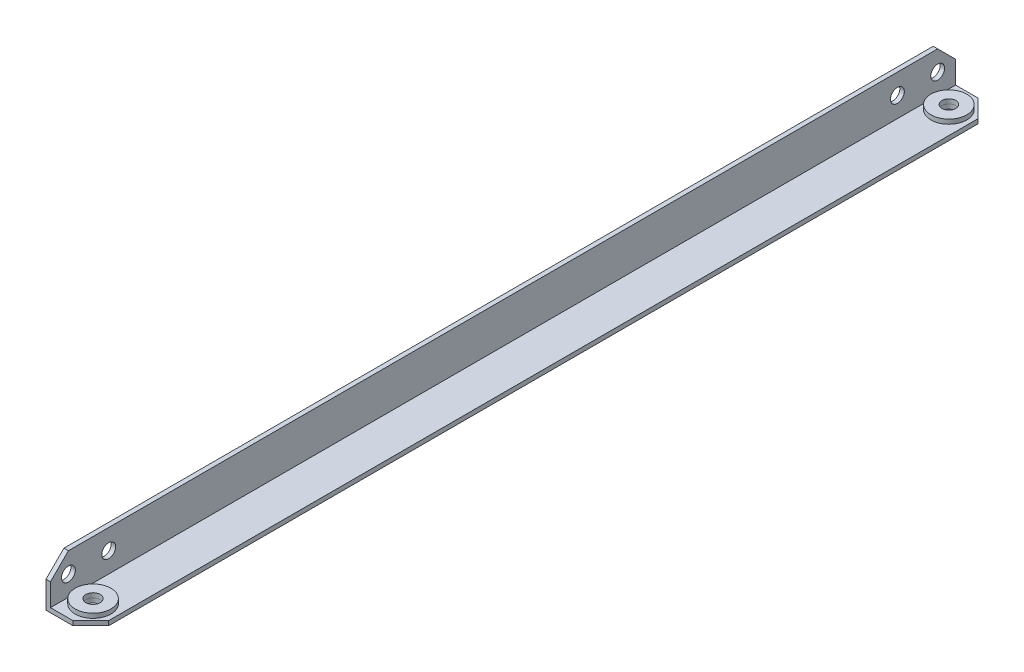
SolidWorks part; units mm, degrees
ref_plane "前视基准面" through (0, 0, 0) normal (0, 0, 1) x (1, 0, 0)
ref_plane "上视基准面" through (0, 0, 0) normal (0, 1, 0) x (1, 0, 0)
ref_plane "右视基准面" through (0, 0, 0) normal (1, 0, 0) x (0, 0, -1)
sketch "草图1" plane through (0, 0, 0) normal (0, 0, 1) x (1, 0, 0)
  line L1 (0, 0) -> (100, 0)
  line L2 (0, 0) -> (0, 100)
  line L3 (0, 100) -> (100, 100)
  line L4 (100, 0) -> (100, 100)
  dimension "D1" = 100
  dimension "D2" = 100
extrude "拉伸1" add sketch "草图1" along normal blind 2020
sketch "草图2" plane through (0, 0, 2020) normal (0, 0, 1) x (1, 0, 0)
  line L0 (0, 0) -> (100, 0) construction
  line L1 (100, 100) -> (10, 100)
  line L2 (100, 100) -> (100, 10)
  line L3 (100, 10) -> (10, 10)
  line L4 (10, 100) -> (10, 10)
  line L5 (0, 100) -> (0, 0) construction
  dimension "D1" = 10
  dimension "D2" = 10
extrude "拉伸2" cut sketch "草图2" against normal through all
sketch "草图3" plane through (10, 0, 0) normal (1, 0, 0) x (0, 0, -1)
  line L1 (-2020, 100) -> (-2020, 10) construction
  line L2 (-1010, -472.1094) -> (-1010, 49527.8906) construction
  line L3 (0, 100) -> (0, 10) construction
  line L4 (0, 10) -> (-2020, 10) construction
  circle A0 centre (-1980, 55) radius 15.5
  circle A1 centre (-1890, 55) radius 15.5
  circle A2 centre (-130, 55) radius 15.5
  circle A3 centre (-40, 55) radius 15.5
  point P14 (-2020, 55)
  dimension "D1" = 130
  dimension "D4" = 31
  dimension "D3" = 31
  dimension "D2" = 1010
  dimension "D5" = 40
  dimension "D6" = 45
  dimension "D7" = 90
extrude "拉伸3" cut sketch "草图3" against normal through all
sketch "草图7" plane through (0, 10, 0) normal (0, 1, 0) x (1, 0, 0)
  line L0 (10, -2020) -> (100, -2020) construction
  line L1 (0, -2020) -> (0, 0) construction
  circle A0 centre (50, -1965) radius 40
  dimension "D3" = 80
  dimension "D1" = 55
  dimension "D2" = 50
extrude "拉伸11" add sketch "草图7" along normal blind 10 separate body
sketch "草图8" plane through (0, 10, 0) normal (0, 1, 0) x (1, 0, 0)
  line L0 (10, 0) -> (10, -2020) construction
  line L1 (10, 0) -> (100, 0) construction
  circle A0 centre (50, -55) radius 40
  dimension "D3" = 80
  dimension "D1" = 40
  dimension "D2" = 55
extrude "拉伸14" add sketch "草图8" along normal blind 10 separate body
sketch "草图9" plane through (0, 20, 0) normal (0, 1, 0) x (1, 0, 0)
  circle A4 centre (50, -55) radius 15.5
  circle A5 centre (50, -55) radius 15.5
  dimension "D1" = 24.5
extrude "拉伸17" cut sketch "草图9" against normal through all
sketch "草图11" plane through (0, 20, 0) normal (0, 1, 0) x (1, 0, 0)
  circle A2 centre (50, -1965) radius 16
  circle A3 centre (50, -1965) radius 16
  dimension "D1" = 24
extrude "拉伸18" cut sketch "草图11" against normal through all
sketch "草图15" plane through (0, 10, 0) normal (0, 1, 0) x (1, 0, 0)
  line L0 (60, -2020) -> (100, -1980)
  line L1 (10, -2020) -> (100, -2020) construction
  line L2 (100, 0) -> (100, -2020) construction
  dimension "D1" = 40
  dimension "D2" = 40
extrude "拉伸20" cut sketch "草图15" against normal through all and the other way through all flip side to cut
sketch "草图17" plane through (0, 10, 0) normal (0, 1, 0) x (1, 0, 0)
  line L0 (60, 0) -> (100, -40)
  line L1 (10, 0) -> (100, 0) construction
  line L2 (100, 0) -> (100, -1980) construction
  dimension "D1" = 40
  dimension "D2" = 40
extrude "拉伸21" cut sketch "草图17" against normal through all and the other way through all
sketch "草图18" plane through (10, 0, 0) normal (1, 0, 0) x (0, 0, -1)
  line L0 (-40, 100) -> (0, 60)
  line L1 (0, 100) -> (-2020, 100) construction
  line L2 (0, 100) -> (0, 10) construction
  dimension "D1" = 40
  dimension "D2" = 40
extrude "拉伸22" cut sketch "草图18" against normal through all and the other way through all
sketch "草图19" plane through (10, 0, 0) normal (1, 0, 0) x (0, 0, -1)
  line L0 (-2020, 60) -> (-1980, 100)
  line L1 (-2020, 100) -> (-2020, 10) construction
  line L2 (-40, 100) -> (-2020, 100) construction
  dimension "D1" = 40
  dimension "D2" = 40
extrude "拉伸23" cut sketch "草图19" against normal through all and the other way through all
